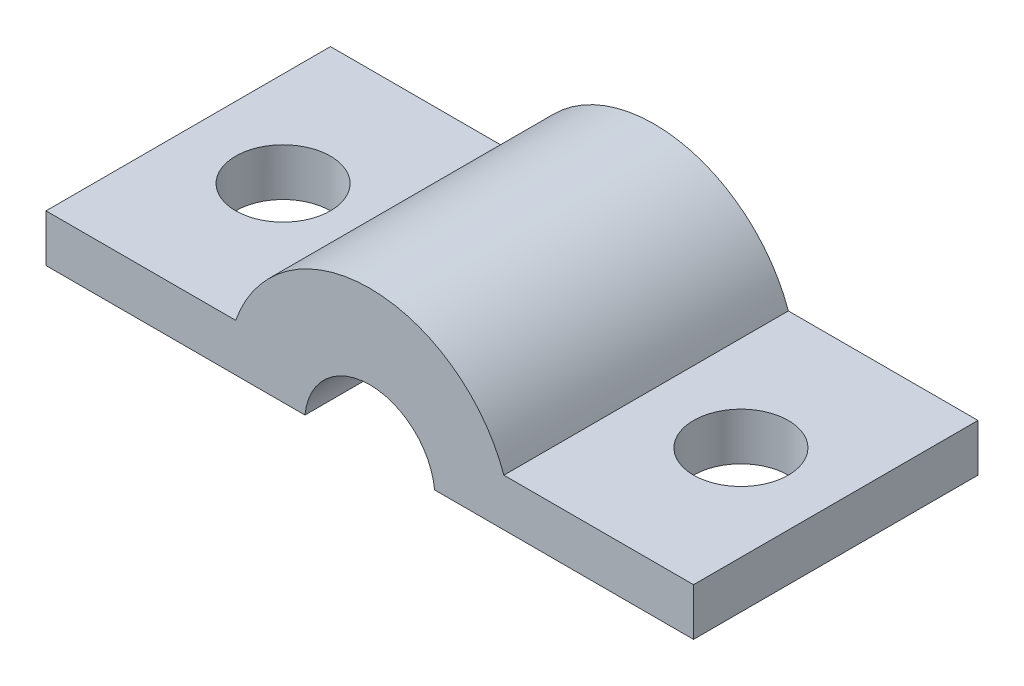
SolidWorks part; units mm, degrees
ref_plane "Front Plane" through (0, 0, 0) normal (0, 0, 1) x (1, 0, 0)
ref_plane "Top Plane" through (0, 0, 0) normal (0, 1, 0) x (1, 0, 0)
ref_plane "Right Plane" through (0, 0, 0) normal (1, 0, 0) x (0, 0, -1)
sketch "Sketch1" plane through (0, 0, 0) normal (0, 0, 1) x (1, 0, 0)
  line L0 (0, 0) -> (10.2426, 0) construction
  line L1 (0, 0) -> (-10.2426, 0) construction
  line L2 (2.05, 0) -> (10.2426, 0)
  line L3 (-2.05, 0) -> (-10.2426, 0)
  line L4 (10.2426, 0) -> (10.2426, 1.5)
  line L5 (10.2426, 1.5) -> (4.2426, 1.5)
  line L6 (-10.2426, 0) -> (-10.2426, 1.5)
  line L7 (-10.2426, 1.5) -> (-4.2426, 1.5)
  arc A1 (4.2426, 1.5) -> (-4.2426, 1.5) centre (0, 0) ccw
  arc A2 (-2.05, 0) -> (2.05, 0) centre (0, -0.2027) cw
  dimension "D2" = 9
  dimension "D7" = 2.06
  dimension "D3" = 6
  dimension "D4" = 6
  dimension "D5" = 1.5
  dimension "D6" = 1.5
extrude "Boss-Extrude1" add sketch "Sketch1" along normal blind 9
sketch "Sketch2" plane through (0, 1.5, 0) normal (0, 1, 0) x (1, 0, 0)
  line L0 (-4.2426, 0) -> (-10.2426, 0) construction
  line L1 (-10.2426, -9) -> (-10.2426, 0) construction
  line L2 (10.2426, -9) -> (4.2426, -9) construction
  line L3 (10.2426, -9) -> (10.2426, 0) construction
  circle A0 centre (-7.2426, -4.5) radius 1.5
  circle A1 centre (7.2426, -4.5) radius 1.5
  dimension "D3" = 3
  dimension "D4" = 3
  dimension "D1" = 4.5
  dimension "D2" = 3
  dimension "D5" = 4.5
  dimension "D6" = 3
extrude "Cut-Extrude1" cut sketch "Sketch2" against normal blind 10
